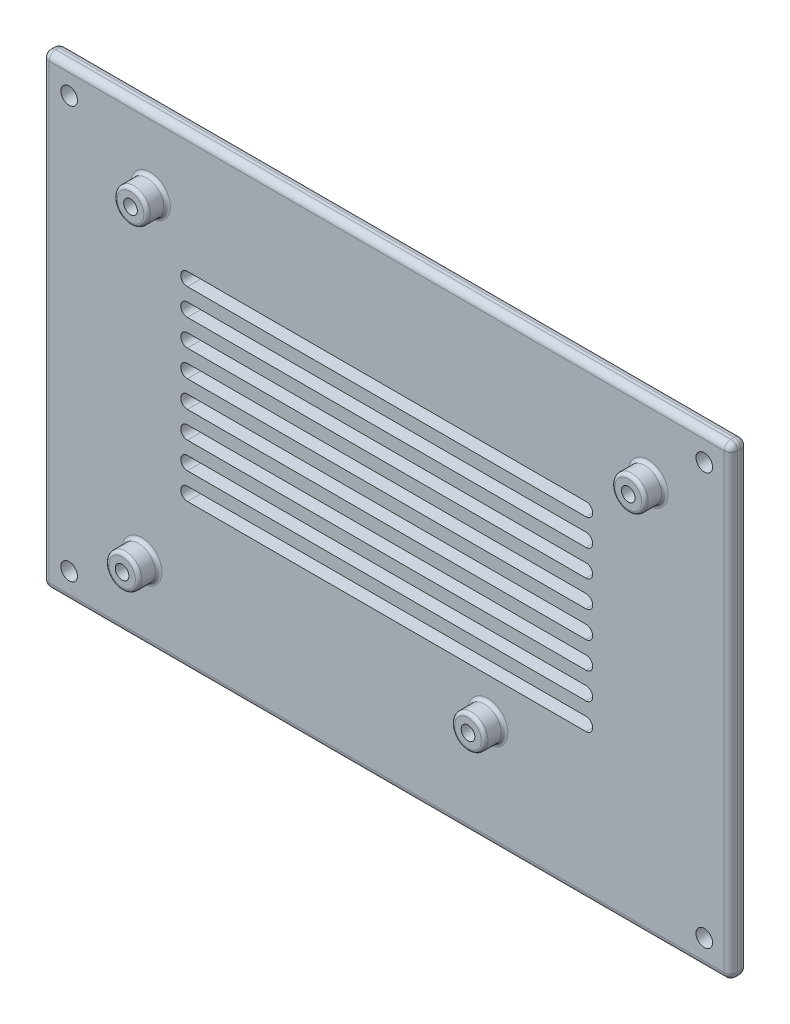
SolidWorks part; units mm, degrees
ref_plane "Plan de face" through (0, 0, 0) normal (0, 0, 1) x (1, 0, 0)
ref_plane "Plan de dessus" through (0, 0, 0) normal (0, 1, 0) x (1, 0, 0)
ref_plane "Plan de droite" through (0, 0, 0) normal (1, 0, 0) x (0, 0, -1)
sketch "Esquisse1" plane through (0, 0, 0) normal (0, 0, 1) x (1, 0, 0)
  line L1 (-51.8, 35) -> (51.8, 35)
  line L2 (-51.8, 35) -> (-51.8, -35)
  line L3 (-51.8, -35) -> (51.8, -35)
  line L4 (51.8, 35) -> (51.8, -35)
  line L5 (-51.8, 35) -> (51.8, -35) construction
  line L6 (-51.8, -35) -> (51.8, 35) construction
  point P0 (0, 0)
  point P5 (0, 0)
  point P13 (0, 0)
  dimension "D1" = 70
  dimension "D2" = 103.6
extrude "Boss.-Extru.1" add sketch "Esquisse1" along normal blind 2.5
fillet "Congé3" radius 1 12 edges at (-51.8, 0, 2.5) (0, -35, 2.5) (0, 35, 2.5) (51.8, 0, 2.5) (51.8, -35, 1.25) (51.8, 35, 1.25) (-51.8, 35, 1.25) (-51.8, -35, 1.25) (51.8, 0, 0) (0, 35, 0) (-51.8, 0, 0) (0, -35, 0)
sketch "Esquisse48" plane through (0, 0, 2.5) normal (0, 0, 1) x (1, 0, 0)
  line L0 (51.8, 34) -> (51.8, -34) construction
  line L1 (-50.8, 35) -> (50.8, 35) construction
  line L2 (50.8, -35) -> (-50.8, -35) construction
  line L3 (-50.8, -35) -> (50.8, -35) construction
  line L6 (-51.8, -34) -> (-51.8, 34) construction
  circle A0 centre (-47.8, 31) radius 3
  circle A1 centre (-47.8, -31) radius 3
  circle A2 centre (47.8, 31) radius 3.3164
  circle A3 centre (47.8, -31) radius 3.4515
  dimension "D1" = 4
  dimension "D2" = 4
  dimension "D3" = 4
  dimension "D4" = 4
  dimension "D5" = 4
  dimension "D6" = 4
  dimension "D7" = 4
  dimension "D8" = 4
hole_wizard "Trou pour taraudage pour trou taraudé M312" positions "Esquisse3D16" profile "Esquisse49" hole size "M3" standard "AS"
sketch3d "Esquisse3D16"
  point P0 (-47.8, 31, 2.5)
  point P3 (-47.8, -31, 2.5)
  point P6 (47.8, -31, 2.5)
  point P9 (47.8, 31, 2.5)
sketch "Esquisse49" plane through (-47.8, 31, 2.5) normal (1, 0, 0) x (0, -1, 0)
  line L0 (0, 0) -> (0, 5.7511)
  line L1 (0, 5.7511) -> (1.25, 5)
  line L2 (1.25, 5) -> (1.25, 0)
  line L5 (1.25, 0) -> (0, 0)
  line L10 (0, 5.7511) -> (-1.25, 5) construction
  line L11 (0, -6.35) -> (0, 107.95) construction
  dimension "Diamètre du perçage" = 2.5
  dimension "Profondeur du perçage" = 5
  dimension "Angle de pointe" = 118
sketch "Esquisse50" plane through (0, 0, 2.5) normal (0, 0, 1) x (1, 0, 0)
  line L0 (30, 0) -> (-30, 0) construction
  line L1 (-51.8, 27.67) -> (51.8, 27.67)
  line L2 (-51.8, 27.67) -> (-51.8, -27.67)
  line L3 (-51.8, -27.67) -> (51.8, -27.67)
  line L4 (51.8, 27.67) -> (51.8, -27.67)
  line L5 (-51.8, 27.67) -> (51.8, -27.67) construction
  line L6 (-51.8, -27.67) -> (51.8, 27.67) construction
  line L7 (30, -1) -> (-30, -1)
  line L8 (30, 1) -> (-30, 1)
  arc A0 (30, -1) -> (30, 1) centre (30, 0) ccw
  arc A1 (-30, 1) -> (-30, -1) centre (-30, 0) ccw
  point P0 (0, 0)
  point P8 (0, 0)
  dimension "D1" = 55.34
  dimension "D2" = 103.6
sketch "Esquisse51" plane through (0, 0, 2.5) normal (0, 0, 1) x (1, 0, 0)
  line L0 (-51.8, 27.67) -> (-51.8, -27.67) construction
  line L1 (-51.8, -27.67) -> (51.8, -27.67) construction
  circle A0 centre (-36.83, -24.13) radius 2.5
  circle A1 centre (15.24, -19.05) radius 2.5
  circle A2 centre (-35.56, 24.13) radius 2.5
  circle A3 centre (39.37, 24.13) radius 2.5
  dimension "D1" = 14.97
  dimension "D2" = 3.54
  dimension "D3" = 67.04
  dimension "D4" = 8.62
  dimension "D5" = 51.8
  dimension "D6" = 16.24
  dimension "D7" = 51.8
  dimension "D8" = 91.17
extrude "Boss.-Extru.13" add sketch "Esquisse51" along normal blind 3 contours A3 | A1 | A2 | A0
sketch "Esquisse52" plane through (0, 0, 5.5) normal (0, 0, 1) x (1, 0, 0)
  circle A0 centre (-36.83, -24.13) radius 1.025
  circle A1 centre (15.24, -19.05) radius 1.025
  circle A2 centre (39.37, 24.13) radius 1.025
  circle A3 centre (-35.56, 24.13) radius 1.025
extrude "Enlèv. mat.-Extru.1" cut sketch "Esquisse52" against normal blind 5.5
extrude "Enlèv. mat.-Extru.2" cut sketch "Esquisse50" against normal blind 5 contours L8 A1 L7 A0
pattern_linear "Répétition linéaire1" count 5 spacing 4 along (0, 1, 0) count 4 spacing 4 along (0, -1, 0) of "Enlèv. mat.-Extru.2"
fillet "Congé4" radius 0.5 8 edges at (17.74, -19.05, 5.5) (41.87, 24.13, 5.5) (-33.06, 24.13, 5.5) (-34.33, -24.13, 5.5) (-34.33, -24.13, 2.5) (-33.06, 24.13, 2.5) (17.74, -19.05, 2.5) (41.87, 24.13, 2.5)
